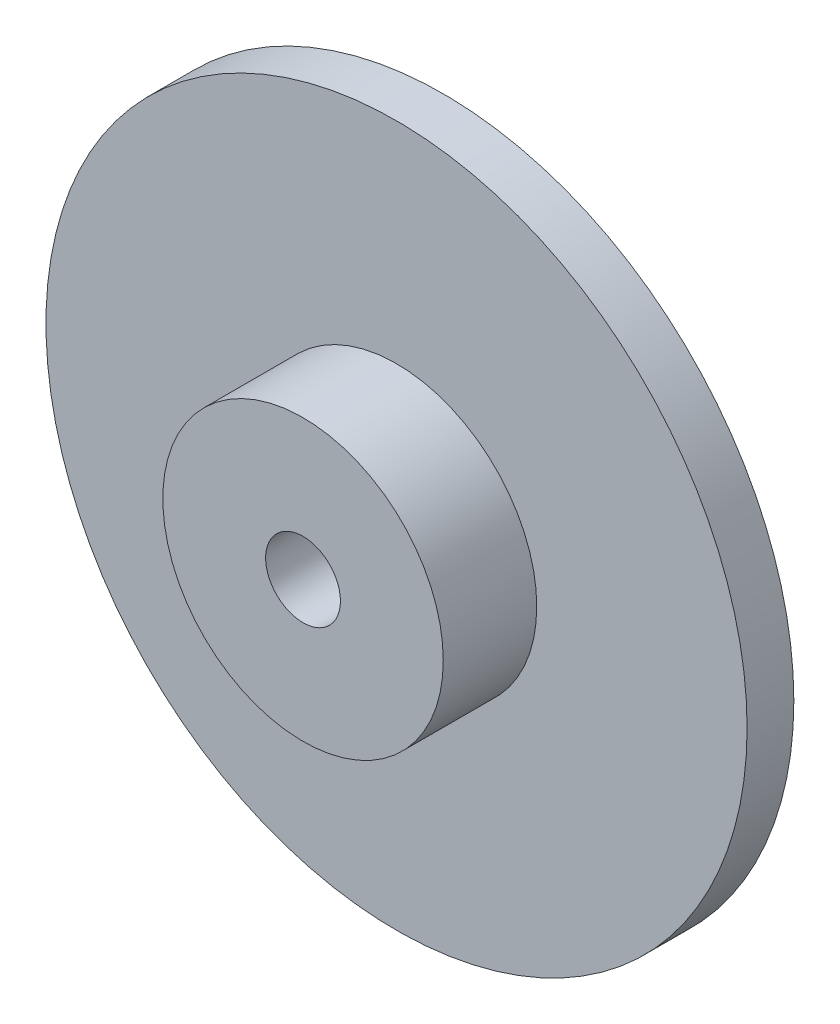
SolidWorks part; units mm, degrees
ref_plane "Front Plane" through (0, 0, 0) normal (0, 0, 1) x (1, 0, 0)
ref_plane "Top Plane" through (0, 0, 0) normal (0, 1, 0) x (1, 0, 0)
ref_plane "Right Plane" through (0, 0, 0) normal (1, 0, 0) x (0, 0, -1)
sketch "Sketch1" plane through (0, 0, 0) normal (0, 0, 1) x (1, 0, 0)
  circle A0 centre (0, 0) radius 75
extrude "Boss-Extrude1" add sketch "Sketch1" along normal blind 10
sketch "Sketch2" plane through (0, 0, 10) normal (0, 0, 1) x (1, 0, 0)
  circle A0 centre (0, 0) radius 30
  point P3 (21.3372, -34.1855)
extrude "Boss-Extrude2" add sketch "Sketch2" along normal blind 20
sketch "Sketch3" plane through (0, 0, 30) normal (0, 0, 1) x (1, 0, 0)
  circle A0 centre (0, 0) radius 8
extrude "Cut-Extrude1" cut sketch "Sketch3" against normal through all
sketch "Sketch4" plane through (0, 0, 30) normal (0, 0, 1) x (1, 0, 0)
  line L1 (-2.5, 11) -> (2.5, 11)
  line L2 (-2.5, 11) -> (-2.5, 5)
  line L3 (-2.5, 5) -> (2.5, 5)
  line L4 (2.5, 11) -> (2.5, 5)
  line L5 (-2.5, 11) -> (2.5, 5) construction
  line L6 (-2.5, 5) -> (2.5, 11) construction
  circle A0 centre (0, 0) radius 8 construction
  point P0 (0, 8)
  dimension "D1" = 6
  dimension "D2" = 5
extrude "Cut-Extrude2" cut sketch "Sketch4" against normal blind 20 from offset 5
